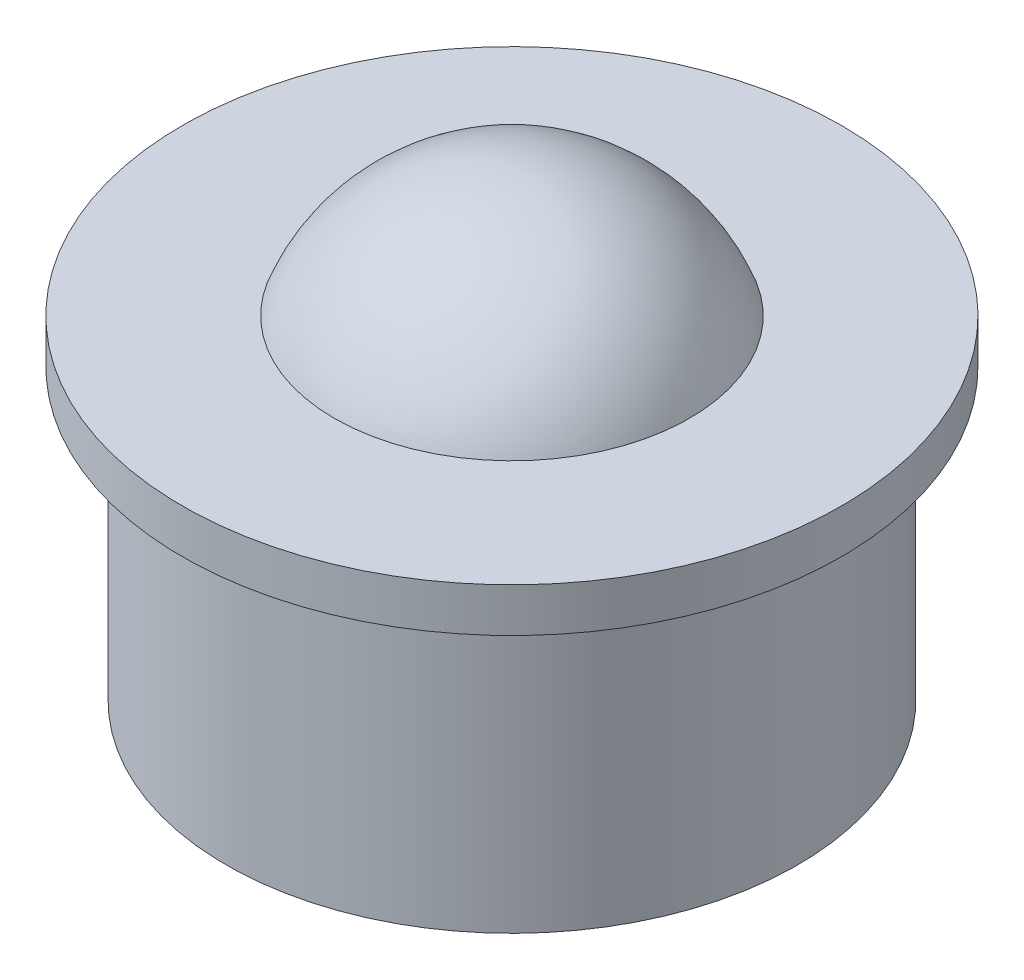
SolidWorks part; units mm, degrees
ref_plane "前视基准面" through (0, 0, 0) normal (0, 0, 1) x (1, 0, 0)
ref_plane "上视基准面" through (0, 0, 0) normal (0, 1, 0) x (1, 0, 0)
ref_plane "右视基准面" through (0, 0, 0) normal (1, 0, 0) x (0, 0, -1)
sketch "草图1" plane through (0, 0, 0) normal (0, 0, 1) x (1, 0, 0)
  line L0 (0, 0) -> (0, 5.8956) construction
  line L1 (0, 4.32) -> (0, -4.32)
  arc A0 (0, -4.32) -> (0, 4.32) centre (0, 0) ccw
revolve "旋转2" add sketch "草图1" angle 360 about L0
sketch "草图2" plane through (0, 0, 0) normal (0, 0, 1) x (1, 0, 0)
  line L0 (0, 1.52) -> (7.5, 1.52)
  line L1 (7.5, 1.52) -> (7.5, 0.52)
  line L2 (7.5, 0.52) -> (6.5, 0.52)
  line L3 (6.5, 0.52) -> (6.5, -6.056)
  line L4 (6.5, -6.056) -> (0, -6.056)
  line L5 (0, -6.056) -> (0, 1.52)
  dimension "D1" = 7.5
  dimension "D2" = 1
  dimension "D3" = 6.5
  dimension "D4" = 1.52
revolve "旋转3" add sketch "草图2" angle 360 about L5
